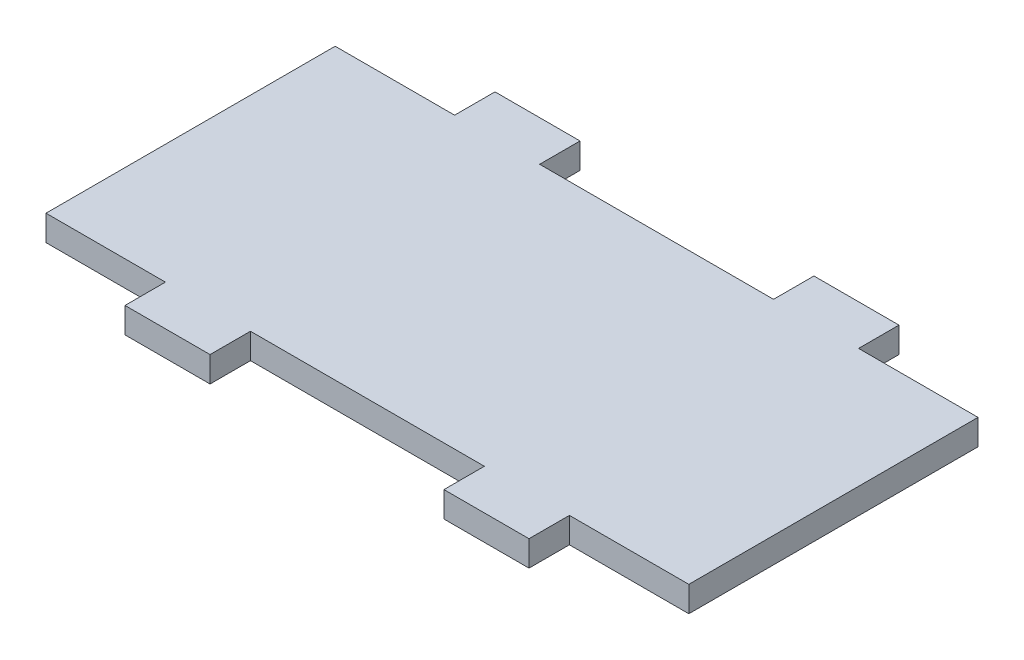
SolidWorks part; units mm, degrees
ref_plane "Front Plane" through (0, 0, 0) normal (0, 0, 1) x (1, 0, 0)
ref_plane "Top Plane" through (0, 0, 0) normal (0, 1, 0) x (1, 0, 0)
ref_plane "Right Plane" through (0, 0, 0) normal (1, 0, 0) x (0, 0, -1)
sketch "Sketch1" plane through (0, 0, 0) normal (0, 1, 0) x (1, 0, 0)
  line L0 (37.79, -17) -> (23.75, -17)
  line L1 (37.79, -17) -> (23.75, -17)
  line L2 (37.79, -17) -> (37.79, 17)
  line L3 (37.79, 17) -> (23.75, 17)
  line L4 (-37.79, -17) -> (-37.79, 17)
  line L5 (37.79, -17) -> (-37.79, 17) construction
  line L6 (37.79, 17) -> (-37.79, -17) construction
  line L7 (-37.79, -17) -> (-23.75, -17)
  line L8 (13.75, -17) -> (-13.75, -17)
  line L9 (-23.75, 17) -> (-37.79, 17)
  line L10 (-13.75, -17) -> (13.75, -17)
  line L11 (-23.75, -17) -> (-37.79, -17)
  line L13 (-23.75, -17) -> (-23.75, -21.75)
  line L14 (-23.75, -21.75) -> (-13.75, -21.75)
  line L15 (-13.75, -17) -> (-13.75, -21.75)
  line L17 (13.75, -17) -> (13.75, -21.75)
  line L18 (13.75, -21.75) -> (23.75, -21.75)
  line L19 (23.75, -17) -> (23.75, -21.75)
  line L21 (-23.75, 17) -> (-23.75, 21.75)
  line L22 (-23.75, 21.75) -> (-13.75, 21.75)
  line L23 (-13.75, 17) -> (-13.75, 21.75)
  line L25 (13.75, 17) -> (13.75, 21.75)
  line L26 (13.75, 21.75) -> (23.75, 21.75)
  line L27 (23.75, 17) -> (23.75, 21.75)
  line L28 (13.75, 17) -> (-13.75, 17)
  point P0 (0, 0)
  dimension "D1" = 27.5
  dimension "D2" = 34
  dimension "D3" = 14.04
  dimension "D4" = 14.04
  dimension "D5" = 10
  dimension "D6" = 10
  dimension "D7" = 4.75
extrude "Boss-Extrude1" add sketch "Sketch1" along normal blind 3 contours L19 L0 L2 L3 L4 L7 L13 L14 L15 L8 L17 L18
